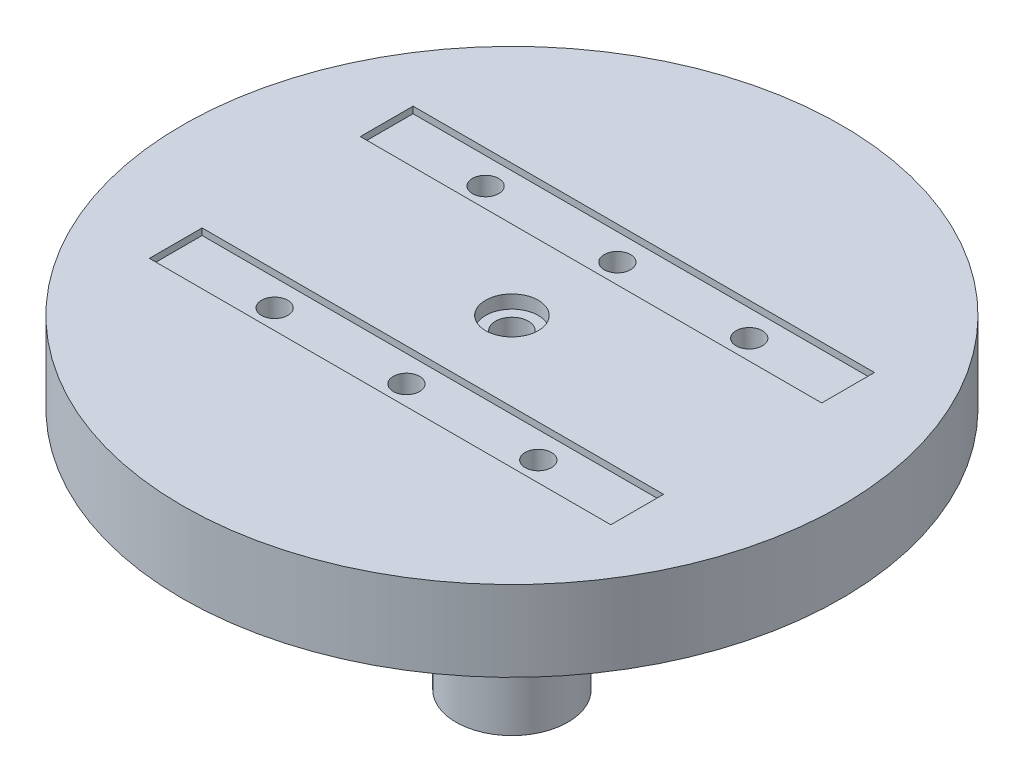
SolidWorks part; units mm, degrees
ref_plane "Front Plane" through (0, 0, 0) normal (0, 0, 1) x (1, 0, 0)
ref_plane "Top Plane" through (0, 0, 0) normal (0, 1, 0) x (1, 0, 0)
ref_plane "Right Plane" through (0, 0, 0) normal (1, 0, 0) x (0, 0, -1)
sketch "Sketch3" plane through (0, 0, 0) normal (0, 1, 0) x (1, 0, 0)
  circle A0 centre (0, 0) radius 50
  dimension "D1" = 100
extrude "Boss-Extrude1" add sketch "Sketch3" along normal blind 12.2
sketch "Sketch4" plane through (0, 12.2, 0) normal (0, 1, 0) x (1, 0, 0)
  line L0 (-62.9978, 16) -> (80.3572, 16) construction
  line L1 (-66.2177, -16) -> (80.3572, -16) construction
  line L3 (-35, -12) -> (35, -12)
  line L4 (-35, -12) -> (-35, -20)
  line L5 (-35, -20) -> (35, -20)
  line L6 (35, -12) -> (35, -20)
  line L7 (-35, -12) -> (35, -20) construction
  line L8 (-35, -20) -> (35, -12) construction
  line L9 (-35, 20) -> (35, 20)
  line L10 (-35, 20) -> (-35, 12)
  line L11 (-35, 12) -> (35, 12)
  line L12 (35, 20) -> (35, 12)
  line L13 (-35, 20) -> (35, 12) construction
  line L14 (-35, 12) -> (35, 20) construction
  point P4 (0, -16)
  point P10 (0, 16)
  dimension "D1" = 16
  dimension "D2" = 16
  dimension "D3" = 70
  dimension "D4" = 8
  dimension "D5" = 8
extrude "Cut-Extrude2" cut sketch "Sketch4" against normal blind 1
sketch "Sketch7" plane through (0, 12.2, 0) normal (0, 1, 0) x (1, 0, 0)
  line L0 (-35, -12) -> (-35, -20) construction
  circle A1 centre (-20, -16) radius 2
  circle A4 centre (0, -16) radius 2
  circle A5 centre (20, -16) radius 2
  circle A6 centre (20, 16) radius 2
  circle A7 centre (0, 16) radius 2
  circle A8 centre (-20, 16) radius 2
  dimension "D3" = 4
  dimension "D2" = 15
  dimension "D4" = 3
extrude "Cut-Extrude4" cut sketch "Sketch7" against normal through all contours A7 | A4 | A1 | A8 | A6 | A5
sketch "Sketch8" plane through (0, 0, 0) normal (0, -1, 0) x (-1, 0, 0)
  circle A0 centre (0, 0) radius 8.5
  dimension "D1" = 17
extrude "Cut-Extrude6" cut sketch "Sketch8" against normal blind 3
sketch "Sketch9" plane through (0, 12.2, 0) normal (0, 1, 0) x (1, 0, 0)
  circle A0 centre (0, 0) radius 4
  dimension "D1" = 8
extrude "Cut-Extrude7" cut sketch "Sketch9" against normal blind 2
sketch "Sketch11" plane through (0, 10.2, 0) normal (0, 1, 0) x (1, 0, 0)
  circle A0 centre (0, 0) radius 2.5
  dimension "D1" = 5
extrude "Cut-Extrude8" cut sketch "Sketch11" against normal through all
sketch "Sketch16" plane through (0, 3, 0) normal (0, -1, 0) x (1, 0, 0)
  circle A0 centre (0, 0) radius 8.5 construction
  circle A1 centre (0, 0) radius 8.5
extrude "Boss-Extrude6" add sketch "Sketch16" along normal blind 40 separate body
sketch "Sketch21" plane through (0, 0, 0) normal (0, -1, 0) x (1, 0, 0)
  circle A2 centre (0, 0) radius 10
  dimension "D2" = 20
extrude "Boss-Extrude11" add sketch "Sketch21" along normal blind 2 separate body
sketch "Sketch22" plane through (0, -2, 0) normal (0, -1, 0) x (1, 0, 0)
  circle A0 centre (0, 0) radius 10 construction
  circle A1 centre (0, 0) radius 10
extrude "Boss-Extrude12" add sketch "Sketch22" along normal blind 2 separate body
sketch "Sketch23" plane through (0, -4, 0) normal (0, -1, 0) x (-1, 0, 0)
  circle A0 centre (0, 0) radius 20
  dimension "D1" = 40
extrude "Boss-Extrude13" add sketch "Sketch23" along normal blind 12 separate body
fillet "Fillet1" radius 2 2 edges at (0, -4, -20) (0, -16, -20)
sketch "Sketch24" plane through (0, -37, 0) normal (0, -1, 0) x (-1, 0, 0)
  circle A0 centre (0, 0) radius 2.5
  circle A1 centre (0, 0) radius 2.25
  dimension "D1" = 5
  dimension "D2" = 4.5
extrude "Boss-Extrude14" add sketch "Sketch24" along normal blind 4
